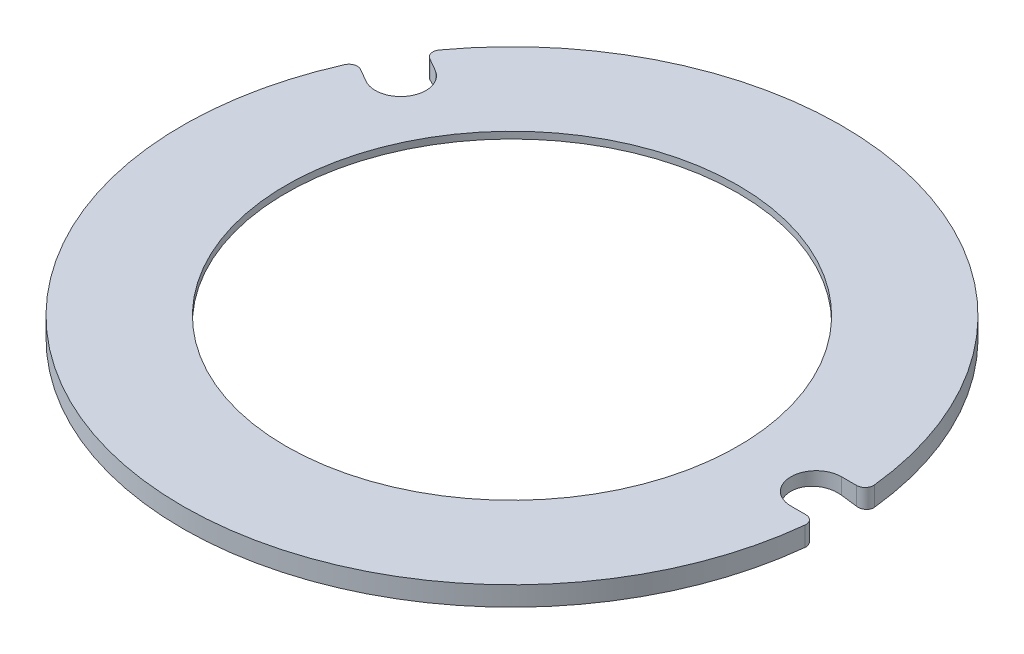
SolidWorks part; units mm, degrees
ref_plane "Front" through (0, 0, 0) normal (0, 0, 1) x (1, 0, 0)
ref_plane "Top" through (0, 0, 0) normal (0, 1, 0) x (1, 0, 0)
ref_plane "Right" through (0, 0, 0) normal (1, 0, 0) x (0, 0, -1)
sketch "Sketch1" plane through (0, 0, 0) normal (0, 0, 1) x (1, 0, 0)
  line L0 (0, 0) -> (0, 270.25) construction
  line L1 (39, 0) -> (39, 270.25) construction
  line L2 (39, 269.7229) -> (26.75, 269.7229)
  line L3 (0, 269.7229) -> (0, 270.25) construction
  line L4 (39, 267.4211) -> (39, 269.7229)
  line L5 (26.75, 269.7229) -> (0, 269.7229) construction
  line L6 (26.75, 269.7229) -> (26.75, 268.9229)
  arc A0 (39, 267.4211) -> (26.75, 268.9229) centre (0, 0) ccw
  arc A1 (26.75, 268.9229) -> (0, 270.25) centre (0, 0) ccw construction
  dimension "D3" = 0.8
  dimension "D1" = 270.25
  dimension "D4" = 26.75
  dimension "D2" = 39
revolve "Revolve1" add sketch "Sketch1" angle 360 about L0
sketch "Sketch2" plane through (0, 0, 0) normal (0, 1, 0) x (1, 0, 0)
  line L0 (36, 0) -> (46, 0) construction
  line L1 (36, 3) -> (46, 3)
  line L2 (36, -3) -> (46, -3)
  line L3 (-31.1769, 18) -> (-39.8372, 23) construction
  line L4 (-32.6769, 15.4019) -> (-41.3372, 20.4019)
  line L5 (-29.6769, 20.5981) -> (-38.3372, 25.5981)
  line L6 (-31.1769, 18) -> (0, 0) construction
  line L7 (0, 0) -> (36, 0) construction
  arc A2 (36, 3) -> (36, -3) centre (36, 0) ccw
  arc A3 (46, -3) -> (46, 3) centre (46, 0) ccw
  arc A4 (-32.6769, 15.4019) -> (-29.6769, 20.5981) centre (-31.1769, 18) ccw
  arc A5 (-38.3372, 25.5981) -> (-41.3372, 20.4019) centre (-39.8372, 23) ccw
  point P2 (41, 0)
  point P13 (-35.507, 20.5)
  dimension "D1" = 6
  dimension "D3" = 2
  dimension "D4" = 150
  dimension "D2" = 10
  dimension "D5" = 36
extrude "Cut-Extrude2" cut sketch "Sketch2" along normal through all
fillet "Fillet1" radius 1 4 edges at (-32.1749, 268.572, -22.0403) (-35.1749, 268.572, -16.8441) (38.8844, 268.572, 3) (38.8844, 268.572, -3)
